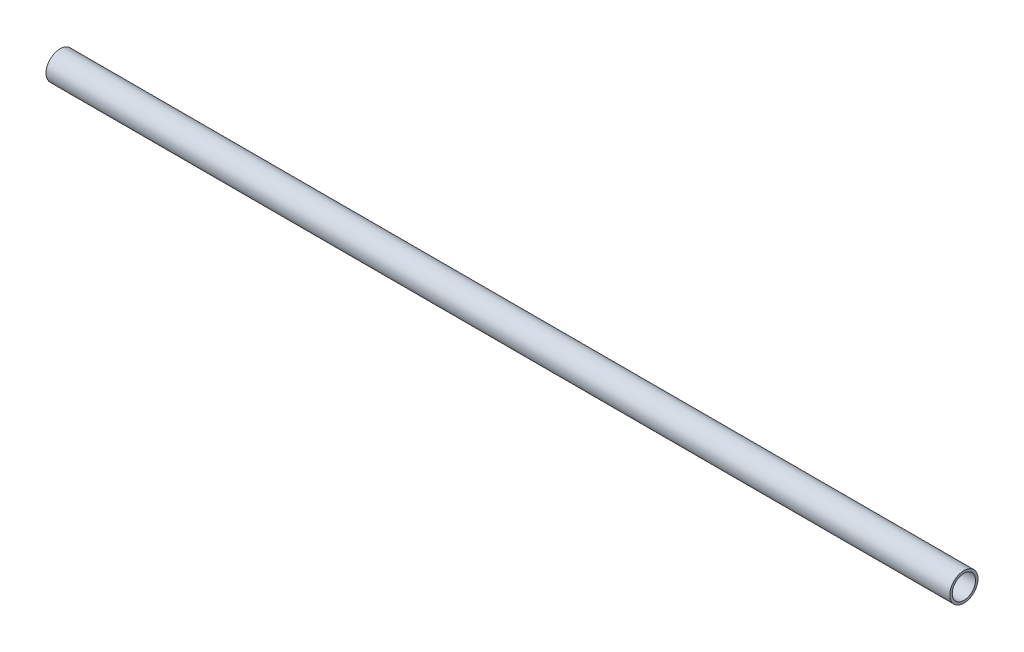
SolidWorks part; units mm, degrees
material "6063-O"
ref_plane "Front Plane" through (0, 0, 0) normal (0, 0, 1) x (1, 0, 0)
ref_plane "Top Plane" through (0, 0, 0) normal (0, 1, 0) x (1, 0, 0)
ref_plane "Right Plane" through (0, 0, 0) normal (1, 0, 0) x (0, 0, -1)
sketch "Sketch1" plane through (0, 0, 0) normal (1, 0, 0) x (0, 0, -1)
  circle A0 centre (0, 0) radius 9.525
  circle A1 centre (0, 0) radius 7.874
  dimension "D1" = 19.05
  dimension "D2" = 1.651
extrude "Boss-Extrude1" add sketch "Sketch1" along normal mid plane 609.6
